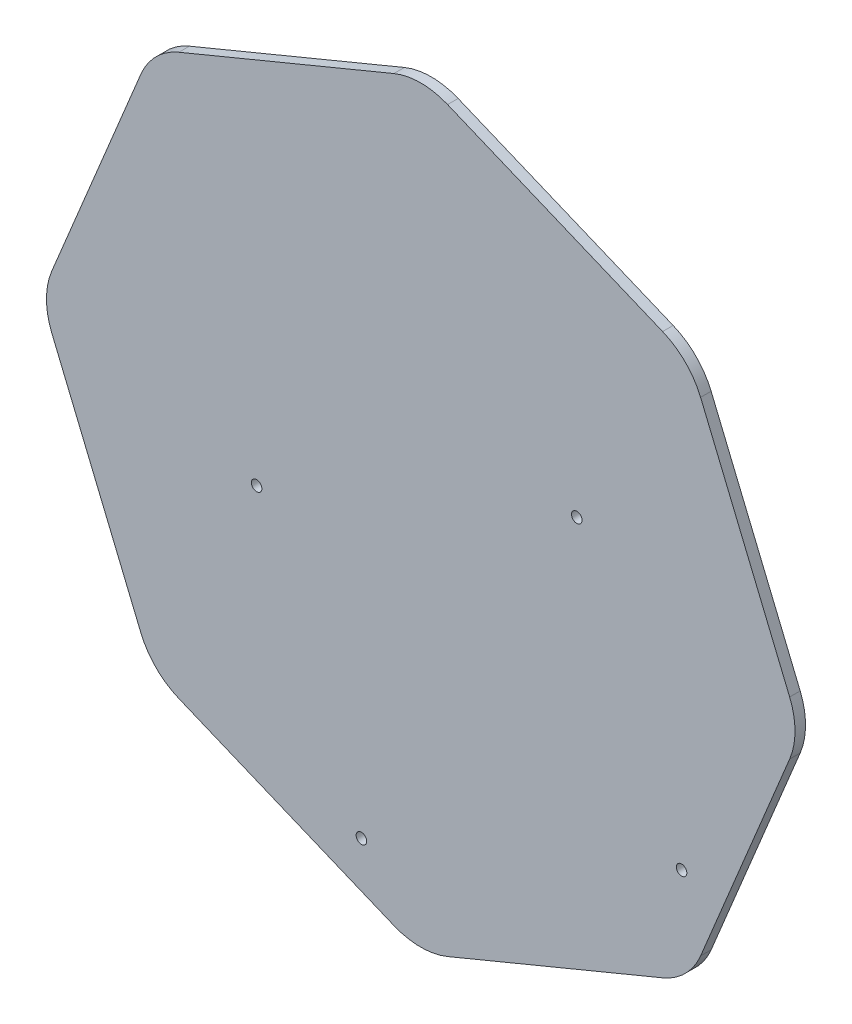
SolidWorks part; units mm, degrees
ref_plane "前视基准面" through (0, 0, 0) normal (0, 0, 1) x (1, 0, 0)
ref_plane "上视基准面" through (0, 0, 0) normal (0, 1, 0) x (1, 0, 0)
ref_plane "右视基准面" through (0, 0, 0) normal (1, 0, 0) x (0, 0, -1)
sketch "草图1" plane through (0, 0, 0) normal (0, 0, 1) x (1, 0, 0)
  line L0 (0, 121.5223) -> (0, -117.9323) construction
  line L1 (-126.6637, 0) -> (129.3981, 0) construction
  line L2 (0, 108.2392) -> (-76.5367, 76.5367)
  line L3 (-76.5367, 76.5367) -> (-108.2392, 0)
  line L4 (-108.2392, 0) -> (-76.5367, -76.5367)
  line L5 (-76.5367, -76.5367) -> (0, -108.2392)
  line L6 (0, -108.2392) -> (76.5367, -76.5367)
  line L7 (76.5367, -76.5367) -> (108.2392, 0)
  line L8 (108.2392, 0) -> (76.5367, 76.5367)
  line L9 (76.5367, 76.5367) -> (0, 108.2392)
  line L10 (-46.7415, -16.1138) -> (-16.8922, -88.1764) construction
  line L11 (-46.7415, -16.1138) -> (44.4454, 21.6571) construction
  line L12 (-16.8922, -88.1764) -> (74.2947, -50.4055) construction
  line L13 (44.4454, 21.6571) -> (74.2947, -50.4055) construction
  circle A0 centre (0, 0) radius 100 construction
  circle A1 centre (-46.7415, -16.1138) radius 1.5
  circle A2 centre (-16.8922, -88.1764) radius 1.5
  circle A3 centre (74.2947, -50.4055) radius 1.5
  circle A4 centre (44.4454, 21.6571) radius 1.5
  dimension "D6" = 3
  dimension "D7" = 3
  dimension "D8" = 3
  dimension "D9" = 3
  dimension "D1" = 200
  dimension "D2" = 78
  dimension "D3" = 98.7
  dimension "D4" = 50.65
  dimension "D5" = 25
extrude "凸台-拉伸1" add sketch "草图1" along normal blind 3
fillet "圆角1" radius 20 8 edges at (-76.5367, 76.5367, 1.5) (0, 108.2392, 1.5) (76.5367, 76.5367, 1.5) (108.2392, 0, 1.5) (76.5367, -76.5367, 1.5) (0, -108.2392, 1.5) (-76.5367, -76.5367, 1.5) (-108.2392, 0, 1.5)
